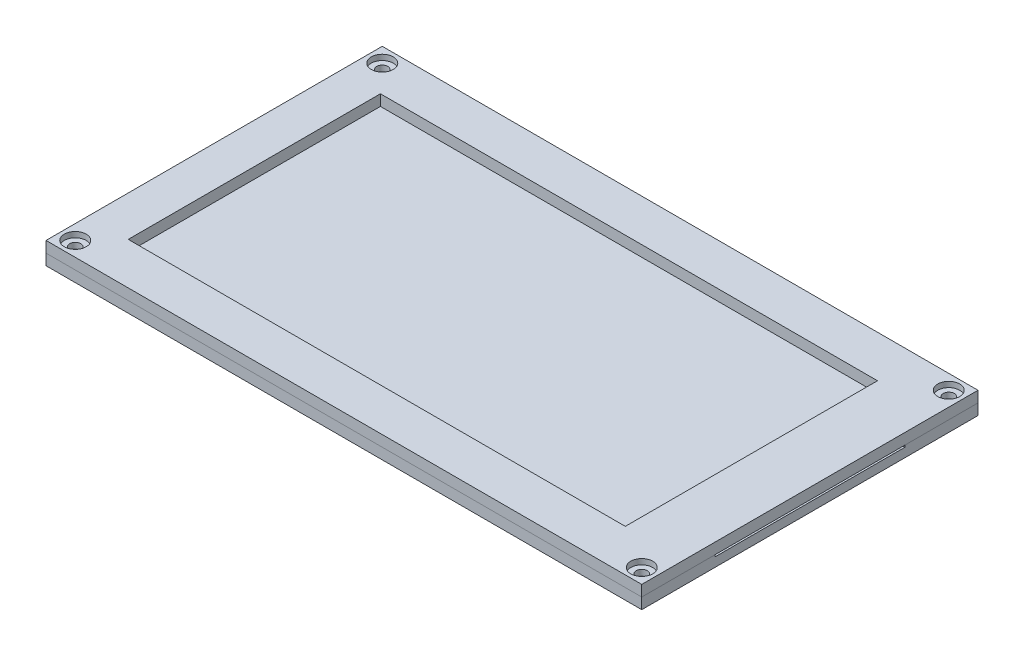
SolidWorks part; units mm, degrees
ref_plane "Front Plane" through (0, 0, 0) normal (0, 0, 1) x (1, 0, 0)
ref_plane "Top Plane" through (0, 0, 0) normal (0, 1, 0) x (1, 0, 0)
ref_plane "Right Plane" through (0, 0, 0) normal (1, 0, 0) x (0, 0, -1)
sketch "Sketch1" plane through (0, 0, 0) normal (0, 1, 0) x (1, 0, 0)
  line L0 (-79, 46) -> (-79, -46)
  line L1 (-68, 34.5) -> (68, 34.5)
  line L2 (-68, 34.5) -> (-68, -34.5)
  line L3 (-68, -34.5) -> (68, -34.5)
  line L4 (68, 34.5) -> (68, -34.5)
  line L5 (-68, 34.5) -> (68, -34.5) construction
  line L6 (-68, -34.5) -> (68, 34.5) construction
  line L7 (-71, 38) -> (76, 38) construction
  line L8 (-71, 38) -> (-71, -38) construction
  line L9 (-71, -38) -> (76, -38) construction
  line L10 (76, 38) -> (76, -38) construction
  line L11 (-71, 38) -> (76, -38) construction
  line L12 (-71, -38) -> (76, 38) construction
  line L13 (-79, -46) -> (84, -46)
  line L14 (84, -46) -> (84, 46)
  line L15 (84, 46) -> (-79, 46)
  line L16 (-71, 38) -> (-79, 46) construction
  line L17 (2.5, 46) -> (2.5, -46) construction
  line L18 (-79, 0) -> (84, 0) construction
  circle A0 centre (-75, 42) radius 1.5
  circle A1 centre (80, 42) radius 1.5
  circle A2 centre (80, -42) radius 1.5
  circle A3 centre (-75, -42) radius 1.5
  point P0 (0, 0)
  point P5 (2.5, 0)
  dimension "D10" = 3
  dimension "D1" = 3
  dimension "D2" = 147
  dimension "D3" = 136
  dimension "D4" = 76
  dimension "D5" = 69
  dimension "D6" = 8
  dimension "D7" = 8
  dimension "D8" = 8
  dimension "D9" = 8
extrude "Boss-Extrude1" add sketch "Sketch1" along normal blind 3
sketch "Sketch2" plane through (0, 3, 0) normal (0, 1, 0) x (1, 0, 0)
  line L0 (2.5, 46) -> (2.5, -46) construction
  line L1 (84, 46) -> (-79, 46) construction
  line L2 (-79, -46) -> (84, -46) construction
  line L3 (-79, 0) -> (84, 0) construction
  line L4 (-79, 46) -> (-79, -46) construction
  line L5 (84, -46) -> (84, 46) construction
  circle A0 centre (-75, 42) radius 3
  circle A1 centre (80, 42) radius 3
  circle A2 centre (80, -42) radius 3
  circle A3 centre (-75, -42) radius 3
  dimension "D1" = 6
extrude "Cut-Extrude1" cut sketch "Sketch2" against normal blind 1.5
sketch "Sketch3" plane through (0, 0, 0) normal (0, -1, 0) x (1, 0, 0)
  line L0 (-79, 46) -> (84, 46)
  line L1 (84, 46) -> (84, -46)
  line L2 (84, -46) -> (-79, -46)
  line L3 (-79, -46) -> (-79, 46)
  line L4 (2.5, 46) -> (2.5, -46) construction
  line L5 (2.5, -46) -> (-79, 0) construction
  line L6 (-79, 0) -> (84, 0) construction
  line L7 (-71.5, 38.5) -> (-71.5, -38.5)
  line L8 (-71.5, -38.5) -> (76.5, -38.5)
  line L9 (76.5, -38.5) -> (76.5, 38.5)
  line L10 (76.5, 38.5) -> (-71.5, 38.5)
  line L11 (76.5, 26) -> (84, 26)
  line L12 (76.5, -26) -> (84, -26)
  circle A0 centre (-75, 42) radius 1.5
  circle A2 centre (-75, 42) radius 1.5 construction
  circle A3 centre (80, 42) radius 1.5
  circle A4 centre (80, -42) radius 1.5
  circle A5 centre (-75, -42) radius 1.5
  line M3 (-79, -46) -> (84, -46)
  line M4 (84, -46) -> (84, 46)
  line M5 (84, 46) -> (-79, 46)
  line M6 (-79, 46) -> (-79, -46)
  circle M11 centre (-75, -42) radius 1.5
  circle M12 centre (80, -42) radius 1.5
  circle M13 centre (80, 42) radius 1.5
  circle M14 centre (-75, 42) radius 1.5
  dimension "D1" = 7.5
  dimension "D2" = 7.5
  dimension "D3" = 7.5
  dimension "D4" = 7.5
  dimension "D5" = 26
extrude "Boss-Extrude2" add sketch "Sketch3" along normal blind 0.5 separate body contours L12 L9 L8 L7 L10 L11 L1 M5 M6 M3 M4 M11 M13 M14 M12
sketch "Sketch4" plane through (0, -0.5, 0) normal (0, -1, 0) x (1, 0, 0)
  line L0 (-79, 46) -> (-79, -46)
  line L1 (-79, -46) -> (84, -46)
  line L2 (-79, -46) -> (84, -46) construction
  line L3 (84, -46) -> (84, -26) construction
  line L4 (84, -46) -> (84, 46)
  line L5 (84, 46) -> (-79, 46)
  line L6 (2.5, 46) -> (2.5, -46) construction
  line L7 (-79, 0) -> (84, 0) construction
  circle A0 centre (-75, 42) radius 1.5
  circle A1 centre (-75, 42) radius 1.5 construction
  circle A2 centre (80, 42) radius 1.5
  circle A3 centre (80, -42) radius 1.5
  circle A4 centre (-75, -42) radius 1.5
extrude "Boss-Extrude3" add sketch "Sketch4" along normal blind 2.5
